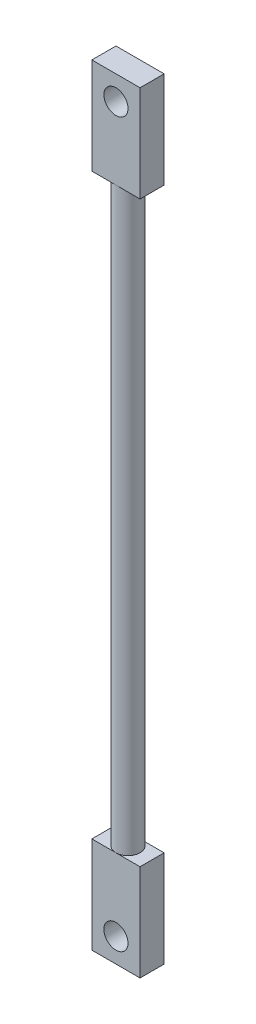
SolidWorks part; units mm, degrees
ref_plane "Front Plane" through (0, 0, 0) normal (0, 0, 1) x (1, 0, 0)
ref_plane "Top Plane" through (0, 0, 0) normal (0, 1, 0) x (1, 0, 0)
ref_plane "Right Plane" through (0, 0, 0) normal (1, 0, 0) x (0, 0, -1)
sketch "Sketch1" plane through (0, 0, 0) normal (0, 1, 0) x (1, 0, 0)
  circle A0 centre (0, 0) radius 1.5875
  dimension "D1" = 3.175
extrude "Boss-Extrude1" add sketch "Sketch1" along normal blind 38.1
sketch "Sketch2" plane through (0, 38.1, 0) normal (0, 1, 0) x (1, 0, 0)
  line L1 (-3.175, -1.5875) -> (3.175, -1.5875)
  line L2 (-3.175, -1.5875) -> (-3.175, 1.5875)
  line L3 (-3.175, 1.5875) -> (3.175, 1.5875)
  line L4 (3.175, -1.5875) -> (3.175, 1.5875)
  line L5 (-3.175, -1.5875) -> (3.175, 1.5875) construction
  line L6 (-3.175, 1.5875) -> (3.175, -1.5875) construction
  circle A0 centre (0, 0) radius 1.5875 construction
  point P0 (0, 0)
  dimension "D1" = 6.35
extrude "Boss-Extrude2" add sketch "Sketch2" along normal blind 12.7
sketch "Sketch3" plane through (0, 0, -1.5875) normal (0, 0, -1) x (-1, 0, 0)
  line L0 (-3.175, 50.8) -> (3.175, 50.8) construction
  circle A0 centre (0, 47.625) radius 1.5875
  dimension "D1" = 3.175
  dimension "D2" = 3.175
extrude "Cut-Extrude1" cut sketch "Sketch3" against normal through all
mirror "Mirror1" about plane through (0, 0, 0) normal (0, 1, 0) of "Boss-Extrude1", "Cut-Extrude1", "Boss-Extrude2"
